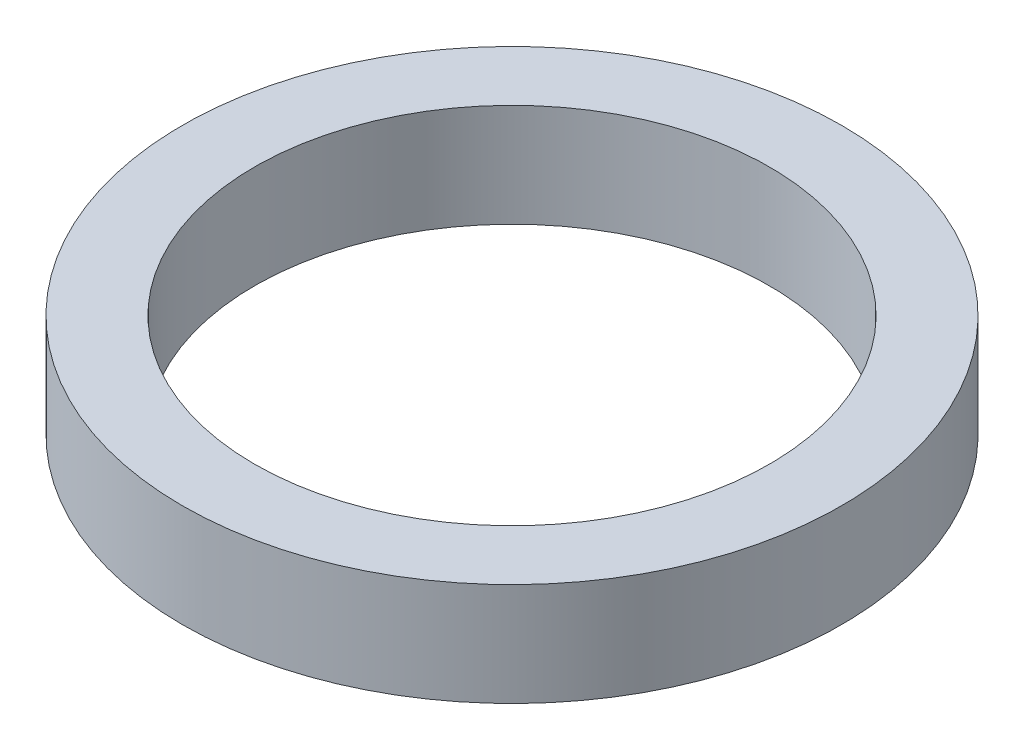
SolidWorks part; units mm, degrees
ref_plane "Front" through (0, 0, 0) normal (0, 0, 1) x (1, 0, 0)
ref_plane "Top" through (0, 0, 0) normal (0, 1, 0) x (1, 0, 0)
ref_plane "Right" through (0, 0, 0) normal (1, 0, 0) x (0, 0, -1)
sketch "Sketch1" plane through (0, 0, 0) normal (0, 1, 0) x (1, 0, 0)
  circle A0 centre (0, 0) radius 8
  dimension "D1" = 16
extrude "Boss-Extrude1" add sketch "Sketch1" along normal blind 2.5
sketch "Sketch5" plane through (0, 2.5, 0) normal (0, 1, 0) x (1, 0, 0)
  circle A0 centre (0, 0) radius 6.25
  dimension "D1" = 12.5
extrude "Cut-Extrude2" cut sketch "Sketch5" against normal mid plane 50
